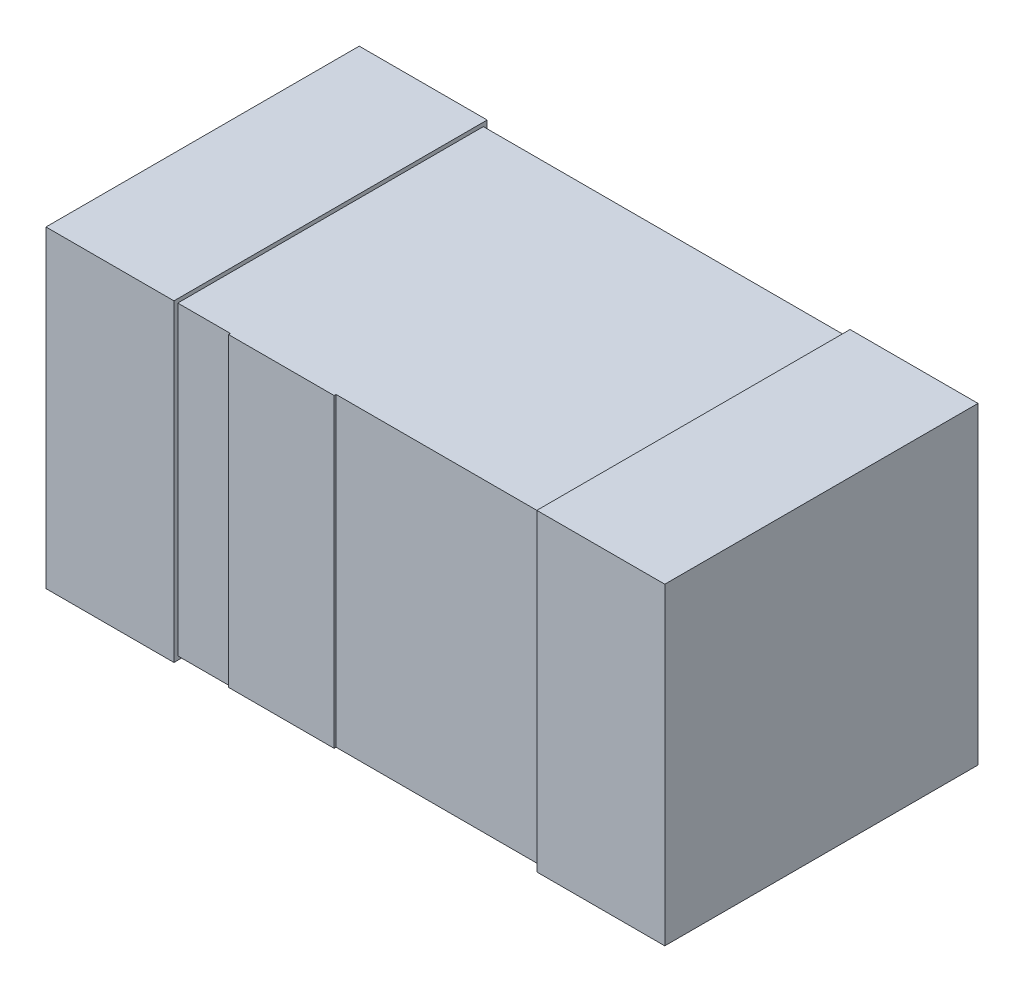
SolidWorks part; units mm, degrees
ref_plane "Front Plane" through (0, 0, 0) normal (0, 0, 1) x (1, 0, 0)
ref_plane "Top Plane" through (0, 0, 0) normal (0, 1, 0) x (1, 0, 0)
ref_plane "Right Plane" through (0, 0, 0) normal (1, 0, 0) x (0, 0, -1)
sketch "Sketch1" plane through (0, 0, 0) normal (0, 0, 1) x (1, 0, 0)
  line L1 (-1.6, 0.8) -> (1.6, 0.8)
  line L2 (-1.6, 0.8) -> (-1.6, -0.8)
  line L3 (-1.6, -0.8) -> (1.6, -0.8)
  line L4 (1.6, 0.8) -> (1.6, -0.8)
  line L5 (-1.6, 0.8) -> (1.6, -0.8) construction
  line L6 (-1.6, -0.8) -> (1.6, 0.8) construction
  point P0 (0, 0)
  dimension "D1" = 3.2
  dimension "D2" = 1.6
extrude "Boss-Extrude1" add sketch "Sketch1" along normal blind 1.6
sketch "Sketch2" plane through (1.6, 0, 0) normal (1, 0, 0) x (0, 0, -1)
  line L0 (-1.6, -0.8) -> (0, -0.8) construction
  line L1 (-1.62, -0.82) -> (0.02, -0.82)
  line L2 (-1.62, -0.82) -> (-1.62, 0.82)
  line L3 (-1.62, 0.82) -> (0.02, 0.82)
  line L4 (0.02, -0.82) -> (0.02, 0.82)
  line L5 (-1.62, -0.82) -> (0.02, 0.82) construction
  line L6 (-1.62, 0.82) -> (0.02, -0.82) construction
  line L7 (-1.6, -0.8) -> (-1.6, 0.8) construction
  point P0 (-0.8, 0)
  point P8 (-0.8, -0.8)
  point P12 (-1.6, 0)
  dimension "D1" = 0.02
  dimension "D2" = 0.02
extrude "Boss-Extrude2" add sketch "Sketch2" against normal blind 0.65 and the other way blind 0.02
mirror "Mirror1" about plane through (0, 0, 0) normal (1, 0, 0) of "Boss-Extrude2"
sketch "Sketch3" plane through (0, 0, 1.6) normal (0, 0, 1) x (1, 0, 0)
  line L0 (-0.95, -0.8) -> (0.95, -0.8) construction
  line L1 (-0.6738, -0.8) -> (-0.1213, -0.8)
  line L2 (-0.6738, -0.8) -> (-0.6738, 0.8)
  line L3 (-0.6738, 0.8) -> (-0.1213, 0.8)
  line L4 (-0.1213, -0.8) -> (-0.1213, 0.8)
  line L5 (0.95, 0.8) -> (-0.95, 0.8) construction
  line L7 (-0.95, -0.8) -> (-0.95, 0.8) construction
  dimension "D1" = 0.5525
  dimension "D2" = 0.2762
extrude "Boss-Extrude3" add sketch "Sketch3" along normal blind 0.01
equation "\"D2@Sketch2\"=\"D1@Sketch2\""
equation "\"D2@Boss-Extrude2\"=\"D1@Sketch2\""
equation "\"A\" = 3.2"
equation "\"B\" = 1.6"
equation "\"C\"= 1.6"
equation "\"D\"= 0.65"
equation "\"D1@Sketch1\"=\"A\""
equation "\"D2@Sketch1\"=\"B\""
equation "\"D1@Boss-Extrude1\"=\"C\""
equation "\"D1@Boss-Extrude2\"=\"D\""
equation "\"D1@Sketch3\"=\"D\"*0.85"
equation "\"D2@Sketch3\"=\"D1@Sketch3\"/2"
equation "\"E\" = 0.35"
